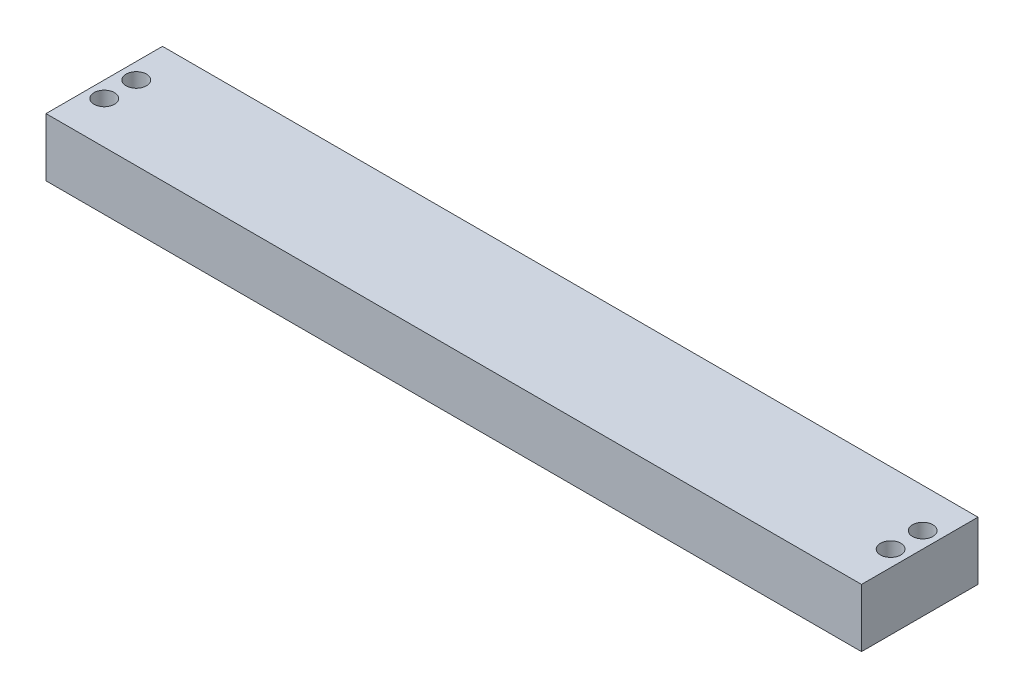
SolidWorks part; units mm, degrees
ref_plane "정면" through (0, 0, 0) normal (0, 0, 1) x (1, 0, 0)
ref_plane "윗면" through (0, 0, 0) normal (0, 1, 0) x (1, 0, 0)
ref_plane "우측면" through (0, 0, 0) normal (1, 0, 0) x (0, 0, -1)
sketch "스케치1" plane through (0, 0, 0) normal (0, 0, 1) x (1, 0, 0)
  line L1 (-140, 10) -> (140, 10)
  line L2 (-140, 10) -> (-140, -10)
  line L3 (-140, -10) -> (140, -10)
  line L4 (140, 10) -> (140, -10)
  line L5 (-140, 10) -> (140, -10) construction
  line L6 (-140, -10) -> (140, 10) construction
  point P0 (0, 0)
  dimension "D1" = 280
  dimension "D2" = 20
extrude "보스-돌출1" add sketch "스케치1" along normal blind 40 contours L1 L4 L3 L2
sketch "스케치2" plane through (0, -10, 0) normal (0, -1, 0) x (1, 0, 0)
  line L3 (-140, 40) -> (-140, 0) construction
  line L4 (140, 40) -> (140, 0) construction
  line L6 (-140, 40) -> (140, 40) construction
  circle A0 centre (-134.5, 25.5) radius 3.5
  circle A1 centre (-134.5, 14.5) radius 3.5
  circle A2 centre (134.5, 24.5) radius 3.5
  circle A3 centre (134.5, 13.5) radius 3.5
  point P14 (-140, 20)
  dimension "D1" = 7
  dimension "D2" = 7
  dimension "D6" = 7
  dimension "D7" = 15.5
  dimension "D8" = 7
  dimension "D3" = 5.5
  dimension "D4" = 5.5
  dimension "D5" = 11
  dimension "D9" = 5.5
  dimension "D10" = 5.5
  dimension "D11" = 5.5
  dimension "D12" = 5.5
extrude "컷-돌출1" cut sketch "스케치2" against normal blind 30
